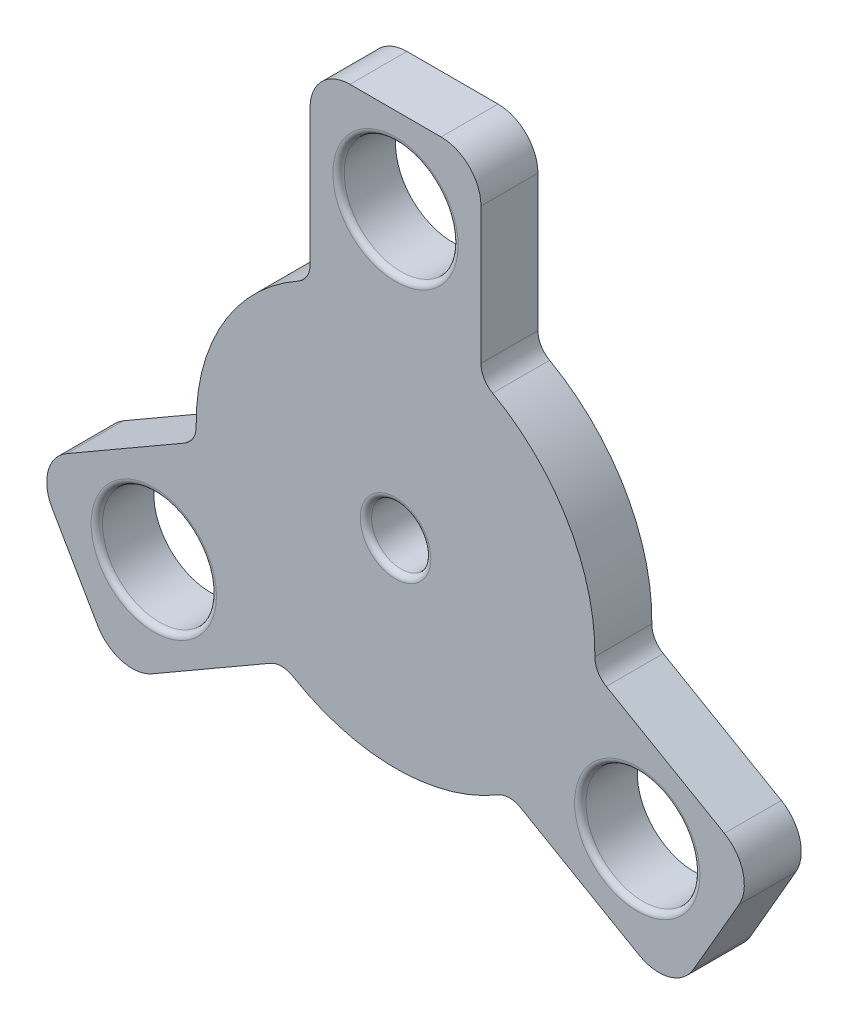
SolidWorks part; units mm, degrees
ref_plane "Front Plane" through (0, 0, 0) normal (0, 0, 1) x (1, 0, 0)
ref_plane "Top Plane" through (0, 0, 0) normal (0, 1, 0) x (1, 0, 0)
ref_plane "Right Plane" through (0, 0, 0) normal (1, 0, 0) x (0, 0, -1)
sketch "Sketch1" plane through (0, 0, 0) normal (0, 0, 1) x (1, 0, 0)
  line L0 (0, 17.5) -> (0, 0) construction
  line L1 (0, 0) -> (-15.1554, -8.75) construction
  line L2 (0, 0) -> (15.1554, -8.75) construction
  line L3 (-7.5, 32.5) -> (-7.5, 15.8114)
  line L4 (7.5, 32.5) -> (7.5, 15.8114)
  line L5 (-7.5, 32.5) -> (7.5, 32.5)
  line L6 (31.8958, -9.7548) -> (17.4431, -1.4105)
  line L7 (24.3958, -22.7452) -> (9.9431, -14.4009)
  line L8 (31.8958, -9.7548) -> (24.3958, -22.7452)
  line L9 (-31.8958, -9.7548) -> (-17.4431, -1.4105)
  line L10 (-24.3958, -22.7452) -> (-9.9431, -14.4009)
  line L11 (-31.8958, -9.7548) -> (-24.3958, -22.7452)
  line L12 (-21.2176, -12.25) -> (-28.1458, -16.25) construction
  line L13 (21.2176, -12.25) -> (28.1458, -16.25) construction
  line L14 (0, 25) -> (0, 30) construction
  line L15 (0, 30) -> (0, 32.5) construction
  circle A0 centre (0, 0) radius 17.5
  circle A1 centre (-21.2176, -12.25) radius 5
  circle A2 centre (21.2176, -12.25) radius 5
  circle A3 centre (0, 25) radius 5
  circle A4 centre (0, 0) radius 2.6
  dimension "D1" = 35
  dimension "D10" = 10
  dimension "D11" = 5.2
  dimension "D2" = 120
  dimension "D3" = 120
  dimension "D4" = 15
  dimension "D5" = 15
  dimension "D12" = 2.5
  dimension "D13" = 8
extrude "Boss-Extrude1" add sketch "Sketch1" along normal blind 5 contours A0 L9 L11 L10 A1 | A0 A4 | A0 L7 L8 L6 A2 | A0 L4 L5 L3 A3
fillet "Fillet1" radius 3.5 6 edges at (24.3958, -22.7452, 2.5) (31.8958, -9.7548, 2.5) (7.5, 32.5, 2.5) (-7.5, 32.5, 2.5) (-31.8958, -9.7548, 2.5) (-24.3958, -22.7452, 2.5)
fillet "Fillet2" radius 2 6 edges at (-17.4431, -1.4105, 2.5) (-7.5, 15.8114, 2.5) (17.4431, -1.4105, 2.5) (7.5, 15.8114, 2.5) (-9.9431, -14.4009, 2.5) (9.9431, -14.4009, 2.5)
fillet "Fillet3" radius 0.5 4 edges at (2.6, 0, 5) (-16.2176, -12.25, 5) (26.2176, -12.25, 5) (5, 25, 5)
